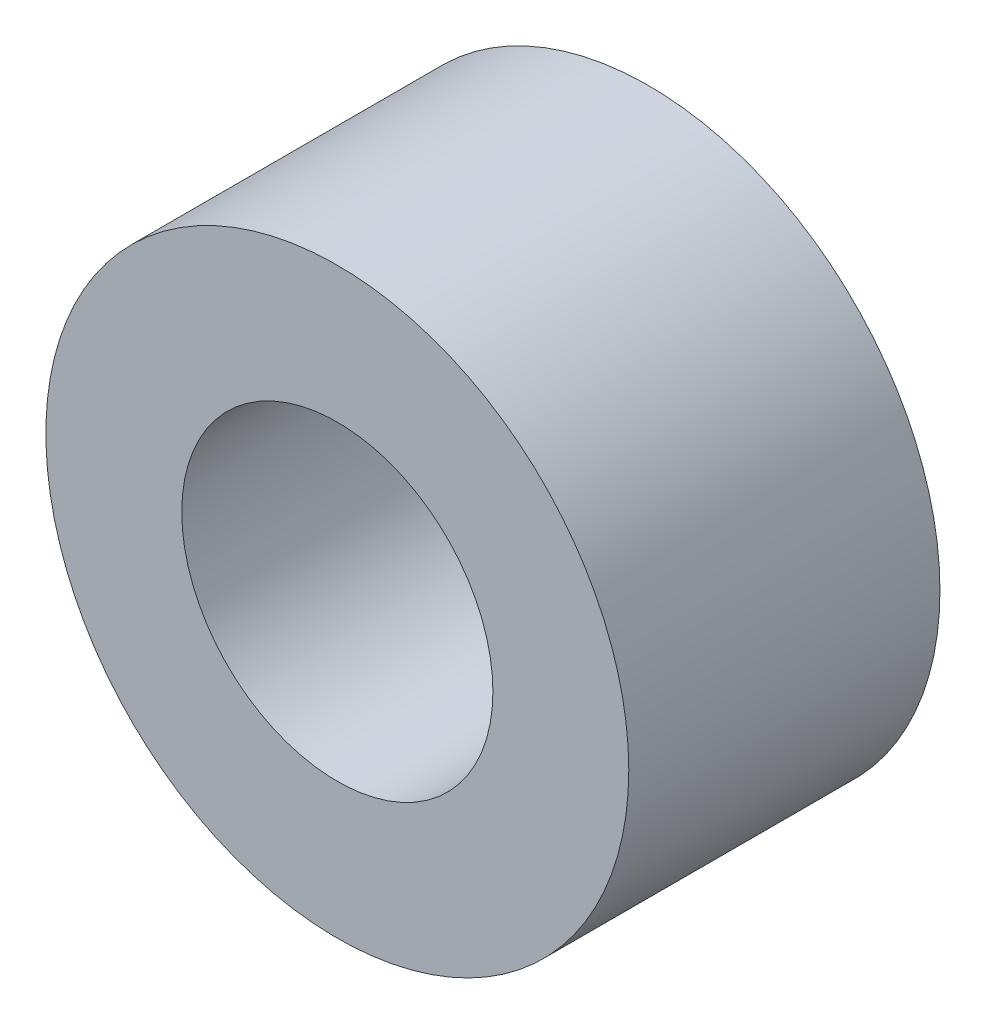
SolidWorks part; units mm, degrees
ref_plane "Front Plane" through (0, 0, 0) normal (1, 0, 0) x (0, 1, 0)
ref_plane "Top Plane" through (0, 0, 0) normal (0, 0, 1) x (0, 1, 0)
ref_plane "Right Plane" through (0, 0, 0) normal (0, 1, 0) x (-1, 0, 0)
sketch "Sketch1" plane through (0, 0, 0) normal (0, 0, 1) x (0, 1, 0)
  circle A0 centre (0, 0) radius 14.05
  circle A1 centre (0, 0) radius 7.5
  dimension "D1" = 28.1
  dimension "D2" = 15
extrude "Boss-Extrude1" add sketch "Sketch1" along normal blind 15
